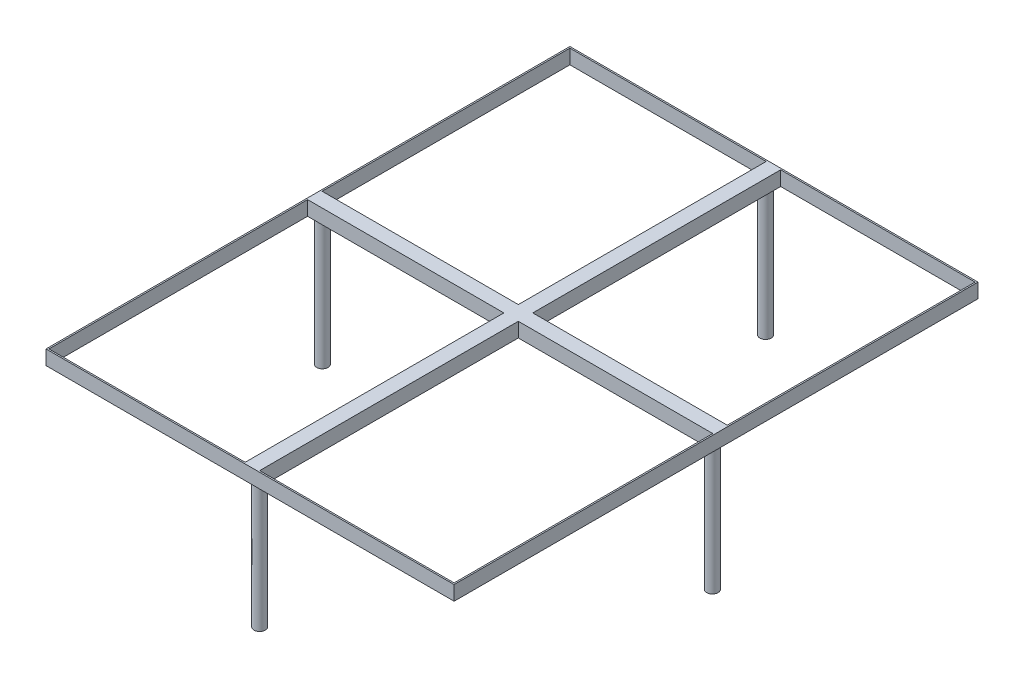
SolidWorks part; units mm, degrees
ref_plane "Alzado" through (0, 0, 0) normal (0, 0, 1) x (1, 0, 0)
ref_plane "Planta" through (0, 0, 0) normal (0, 1, 0) x (1, 0, 0)
ref_plane "Vista lateral" through (0, 0, 0) normal (1, 0, 0) x (0, 0, -1)
sketch "Croquis1" plane through (0, 0, 0) normal (0, 1, 0) x (1, 0, 0)
  line L0 (80.6667, 259.3333) -> (280.6667, 259.3333) construction
  line L1 (-259.3333, 259.3333) -> (-59.3333, 259.3333) construction
  line L2 (-259.3333, 259.3333) -> (-259.3333, -20.6667) construction
  line L3 (-259.3333, -20.6667) -> (-59.3333, -20.6667) construction
  line L4 (-59.3333, 259.3333) -> (-59.3333, -20.6667) construction
  line L5 (-259.3333, 259.3333) -> (-59.3333, -20.6667) construction
  line L6 (-259.3333, -20.6667) -> (-59.3333, 259.3333) construction
  line L7 (80.6667, 259.3333) -> (80.6667, -20.6667) construction
  line L8 (80.6667, -20.6667) -> (280.6667, -20.6667) construction
  line L9 (280.6667, 259.3333) -> (280.6667, -20.6667) construction
  line L10 (80.6667, 259.3333) -> (280.6667, -20.6667) construction
  line L11 (80.6667, -20.6667) -> (280.6667, 259.3333) construction
  line L12 (-259.3333, -160.6667) -> (-59.3333, -160.6667) construction
  line L13 (-259.3333, -160.6667) -> (-259.3333, -440.6667) construction
  line L14 (-259.3333, -440.6667) -> (-59.3333, -440.6667) construction
  line L15 (-59.3333, -160.6667) -> (-59.3333, -440.6667) construction
  line L16 (-259.3333, -160.6667) -> (-59.3333, -440.6667) construction
  line L17 (-259.3333, -440.6667) -> (-59.3333, -160.6667) construction
  line L18 (80.6667, -160.6667) -> (280.6667, -160.6667) construction
  line L19 (80.6667, -160.6667) -> (80.6667, -440.6667) construction
  line L20 (80.6667, -440.6667) -> (280.6667, -440.6667) construction
  line L21 (280.6667, -160.6667) -> (280.6667, -440.6667) construction
  line L22 (80.6667, -160.6667) -> (280.6667, -440.6667) construction
  line L23 (80.6667, -440.6667) -> (280.6667, -160.6667) construction
  line L25 (-269.3333, 269.3333) -> (290.6667, 269.3333)
  line L26 (-269.3333, 269.3333) -> (-269.3333, -450.6667)
  line L27 (-269.3333, -450.6667) -> (290.6667, -450.6667)
  line L28 (290.6667, 269.3333) -> (290.6667, -450.6667)
  line L29 (-271.3333, 271.3333) -> (292.6667, 271.3333)
  line L30 (-271.3333, 271.3333) -> (-271.3333, -452.6667)
  line L31 (-271.3333, -452.6667) -> (292.6667, -452.6667)
  line L32 (292.6667, 271.3333) -> (292.6667, -452.6667)
  point P0 (-159.3333, 119.3333)
  point P5 (180.6667, 119.3333)
  point P10 (-159.3333, -300.6667)
  point P15 (180.6667, -300.6667)
  dimension "D1" = 200
  dimension "D2" = 280
  dimension "D3" = 200
  dimension "D4" = 280
  dimension "D5" = 200
  dimension "D6" = 280
  dimension "D7" = 200
  dimension "D8" = 280
  dimension "D9" = 700
  dimension "D10" = 700
  dimension "D11" = 540
  dimension "D12" = 540
  dimension "D13" = 560
  dimension "D14" = 720
  dimension "D15" = 724
  dimension "D16" = 564
  dimension "D17" = 10
  dimension "D18" = 10
  dimension "D19" = 2
  dimension "D20" = 2
extrude "Saliente-Extruir1" add sketch "Croquis1" along normal blind 20
sketch "Croquis2" plane through (0, 20, 0) normal (0, 1, 0) x (1, 0, 0)
  line L6 (-269.3333, 269.3333) -> (-269.3333, -450.6667) construction
  line L7 (-269.3333, -73.1992) -> (290.6667, -73.1992)
  line L8 (-269.3333, -73.1992) -> (-269.3333, -93.1992)
  line L9 (-269.3333, -93.1992) -> (290.6667, -93.1992)
  line L10 (290.6667, -73.1992) -> (290.6667, -93.1992)
  line L11 (290.6667, -450.6667) -> (290.6667, 269.3333) construction
  line L18 (-269.3333, 269.3333) -> (290.6667, 269.3333) construction
  line L19 (1.9402, 269.3333) -> (21.9402, 269.3333)
  line L20 (1.9402, 269.3333) -> (1.9402, -450.6667)
  line L21 (1.9402, -450.6667) -> (21.9402, -450.6667)
  line L22 (21.9402, 269.3333) -> (21.9402, -450.6667)
  line L23 (-269.3333, -450.6667) -> (290.6667, -450.6667) construction
  point P32 (0, 0)
  line M7 (290.6667, -450.6667) -> (-269.3333, -450.6667)
  line M8 (-269.3333, -450.6667) -> (-269.3333, 269.3333)
  line M9 (-269.3333, 269.3333) -> (290.6667, 269.3333)
  line M10 (290.6667, 269.3333) -> (290.6667, -450.6667)
  dimension "D1" = 20
  dimension "D3" = 20
extrude "Saliente-Extruir4" add sketch "Croquis2" against normal blind 20 contours L22 L9 L20 M7 | L20 L7 L9 M8 | L7 L22 L9 M10 | L22 L20 L7 M9 | L22 L7 L20 L9
sketch "Croquis4" plane through (0, 0, 0) normal (0, -1, 0) x (1, 0, 0)
  circle A0 centre (279.9562, 83.0174) radius 7.808
  circle A2 centre (12.0457, 440.7406) radius 7.808
  circle A3 centre (12.0457, -258.3636) radius 7.808
  circle A4 centre (-258.9827, 83.0174) radius 7.808
  point P4 (261.696, 83.0174)
  point P5 (15.154, 436.8963)
  point P6 (12.0457, 440.7406)
  point P9 (12.0457, -105.1986)
  point P10 (12.0457, -258.3636)
  point P13 (-258.9827, 83.0174)
extrude "Saliente-Extruir5" add sketch "Croquis4" along normal blind 177
